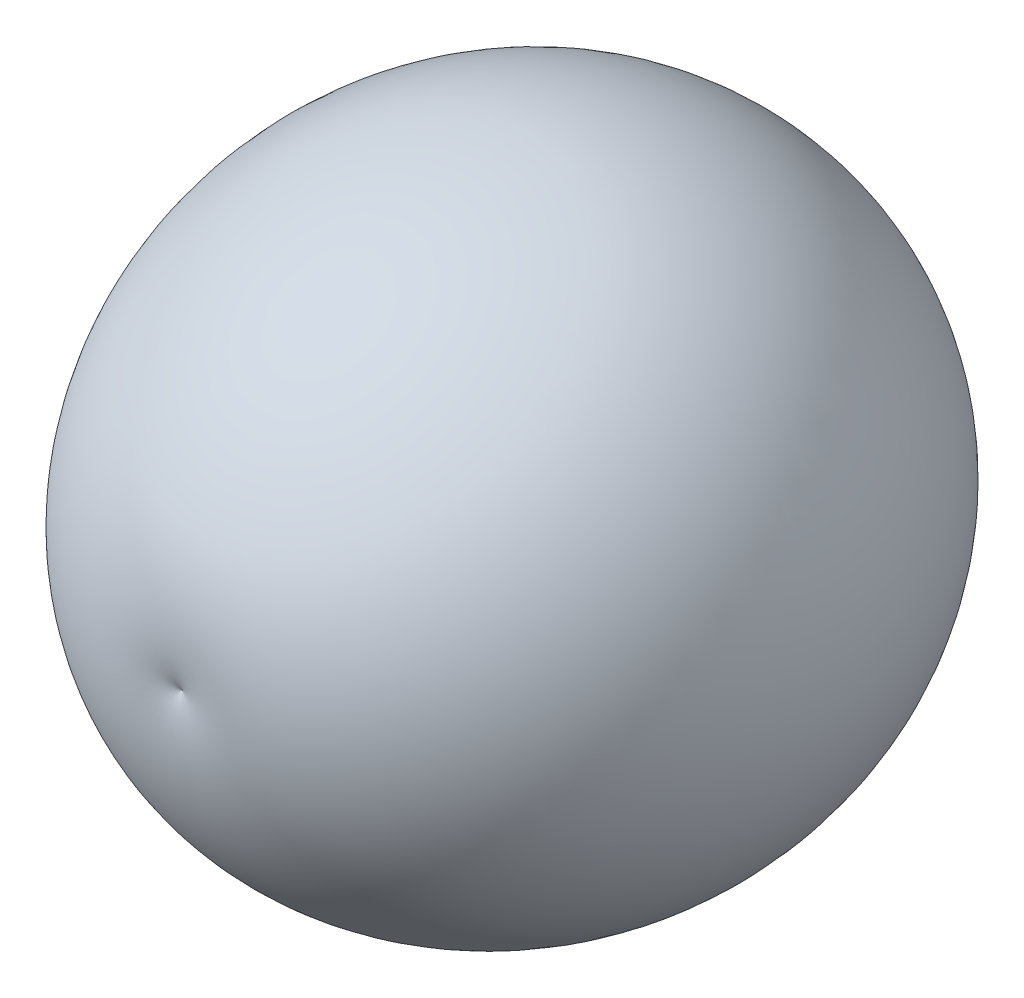
SolidWorks part; units mm, degrees
ref_plane "Front Plane" through (0, 0, 0) normal (0, 0, 1) x (1, 0, 0)
ref_plane "Top Plane" through (0, 0, 0) normal (0, 1, 0) x (1, 0, 0)
ref_plane "Right Plane" through (0, 0, 0) normal (1, 0, 0) x (0, 0, -1)
sketch "Sketch1" plane through (0, 0, 0) normal (0, 1, 0) x (1, 0, 0)
  line L0 (0, 296.9872) -> (0, 0) construction
  line L1 (0, 0) -> (0, 296.9872)
  spline S0 degree 4 poles (0, 0) (0.048, -0.0322) (0.1451, -0.0946) (0.3442, -0.212) (0.6494, -0.3763) (1.0118, -0.5557) (1.4324, -0.7471) (1.858, -0.927) (2.3953, -1.1392) (3.0578, -1.3794) (3.8484, -1.638) (5.0022, -1.9733) (6.4154, -2.3228) (8.0806, -2.6581) (10.0716, -2.9654) (12.1468, -3.1952) (14.3028, -3.3457) (16.5363, -3.4147) (19.7079, -3.3986) (23.0648, -3.2053) (26.5956, -2.8229) (30.289, -2.2374) (33.2255, -1.666) (36.8702, -0.8293) (41.1979, 0.3603) (46.1718, 2.0006) (53.2003, 4.7667) (64.0663, 9.9746) (78.088, 18.8248) (94.078, 32.6027) (109.5221, 51.006) (121.9933, 71.5305) (130.1581, 90.8897) (135.1077, 108.1769) (138.3768, 125.8383) (139.6808, 140.7664) (139.5399, 155.7516) (137.9417, 170.6344) (135.787, 182.4138) (132.7577, 193.9996) (128.8596, 205.3229) (124.1029, 216.3136) (118.5028, 226.8999) (112.0805, 237.009) (104.8638, 246.5678) (96.8872, 255.5029) (88.193, 263.742) (80.0016, 270.2809) (72.6001, 275.365) (66.1993, 279.2352) (60.9479, 282.1039) (55.5751, 284.7382) (50.0906, 287.1316) (44.5048, 289.2779) (38.8285, 291.1716) (33.0724, 292.8077) (27.2485, 294.182) (22.103, 295.1522) (18.0351, 295.7605) (15.0657, 296.1242) (13.2078, 296.3232) (11.717, 296.4655) (10.2308, 296.5907) (8.7323, 296.699) (7.2185, 296.7922) (5.6432, 296.8691) (4.0785, 296.9284) (2.6141, 296.9636) (1.4631, 296.9813) (0.1611, 296.9885) (-0.5495, 296.9871) (-1.6872, 296.9787) (-2.64, 296.9611) (-3.7848, 296.9357) (-4.9886, 296.8947) (-6.447, 296.8322) (-7.8591, 296.754) (-9.2969, 296.6603) (-10.7176, 296.551) (-12.1467, 296.4261) (-13.5686, 296.2857) (-14.9921, 296.1297) (-16.7673, 295.9154) (-18.8946, 295.6273) (-21.3695, 295.2462) (-24.1881, 294.7491) (-26.9951, 294.1909) (-29.7894, 293.572) (-32.5695, 292.8926) (-35.3344, 292.1532) (-38.0826, 291.3542) (-40.8129, 290.4962) (-42.8464, 289.8088) (-44.1952, 289.3312) (-44.8679, 289.0876) knots 0 0 0 0 0 0.000459 0.000917 0.001835 0.002752 0.003669 0.004587 0.005504 0.007339 0.009265 0.011192 0.015044 0.018897 0.02275 0.027185 0.031621 0.036056 0.040492 0.052369 0.058307 0.064245 0.070184 0.076122 0.087999 0.099876 0.111753 0.136079 0.183586 0.231092 0.278599 0.326106 0.373612 0.397366 0.421119 0.468626 0.492379 0.516133 0.539886 0.563639 0.587393 0.611146 0.634899 0.658653 0.682406 0.70616 0.729913 0.753666 0.765543 0.77742 0.789296 0.801173 0.81305 0.824926 0.836803 0.84868 0.860556 0.872433 0.878371 0.881341 0.88431 0.887279 0.890248 0.893217 0.896186 0.899413 0.902639 0.905865 0.907478 0.909091 0.911932 0.913352 0.914773 0.917614 0.920455 0.923295 0.926136 0.928977 0.931818 0.934659 0.9375 0.940341 0.943182 0.948864 0.954545 0.960227 0.965909 0.971591 0.977273 0.982955 0.988636 0.994318 1 1 1 1 1 construction
  spline S1 degree 4 poles (0, 0) (0.048, -0.0322) (0.1451, -0.0946) (0.3442, -0.212) (0.6494, -0.3763) (1.0118, -0.5557) (1.4324, -0.7471) (1.858, -0.927) (2.3953, -1.1392) (3.0578, -1.3794) (3.8484, -1.638) (5.0022, -1.9733) (6.4154, -2.3228) (8.0806, -2.6581) (10.0716, -2.9654) (12.1468, -3.1952) (14.3028, -3.3457) (16.5363, -3.4147) (19.7079, -3.3986) (23.0648, -3.2053) (26.5956, -2.8229) (30.289, -2.2374) (33.2255, -1.666) (36.8702, -0.8293) (41.1979, 0.3603) (46.1718, 2.0006) (53.2003, 4.7667) (64.0663, 9.9746) (78.088, 18.8248) (94.078, 32.6027) (109.5221, 51.006) (121.9933, 71.5305) (130.1581, 90.8897) (135.1077, 108.1769) (138.3768, 125.8383) (139.6808, 140.7664) (139.5399, 155.7516) (137.9417, 170.6344) (135.787, 182.4138) (132.7577, 193.9996) (128.8596, 205.3229) (124.1029, 216.3136) (118.5028, 226.8999) (112.0805, 237.009) (104.8638, 246.5678) (96.8872, 255.5029) (88.193, 263.742) (80.0016, 270.2809) (72.6001, 275.365) (66.1993, 279.2352) (60.9479, 282.1039) (55.5751, 284.7382) (50.0906, 287.1316) (44.5048, 289.2779) (38.8285, 291.1716) (33.0724, 292.8077) (27.2485, 294.182) (22.103, 295.1522) (18.0351, 295.7605) (15.0657, 296.1242) (13.2078, 296.3232) (11.717, 296.4655) (10.2308, 296.5907) (8.7323, 296.699) (7.2185, 296.7922) (5.6432, 296.8691) (4.0785, 296.9284) (2.6141, 296.9636) (1.4631, 296.9813) (0.5591, 296.9863) (0.1846, 296.9872) (0, 296.9872) knots 0 0 0 0 0 0.000459 0.000917 0.001835 0.002752 0.003669 0.004587 0.005504 0.007339 0.009265 0.011192 0.015044 0.018897 0.02275 0.027185 0.031621 0.036056 0.040492 0.052369 0.058307 0.064245 0.070184 0.076122 0.087999 0.099876 0.111753 0.136079 0.183586 0.231092 0.278599 0.326106 0.373612 0.397366 0.421119 0.468626 0.492379 0.516133 0.539886 0.563639 0.587393 0.611146 0.634899 0.658653 0.682406 0.70616 0.729913 0.753666 0.765543 0.77742 0.789296 0.801173 0.81305 0.824926 0.836803 0.84868 0.860556 0.872433 0.878371 0.881341 0.88431 0.887279 0.890248 0.893217 0.896186 0.899413 0.902639 0.905865 0.907478 0.909091 0.909091 0.909091 0.909091 0.909091
revolve "Revolve2" add sketch "Sketch1" angle 360 about L0
